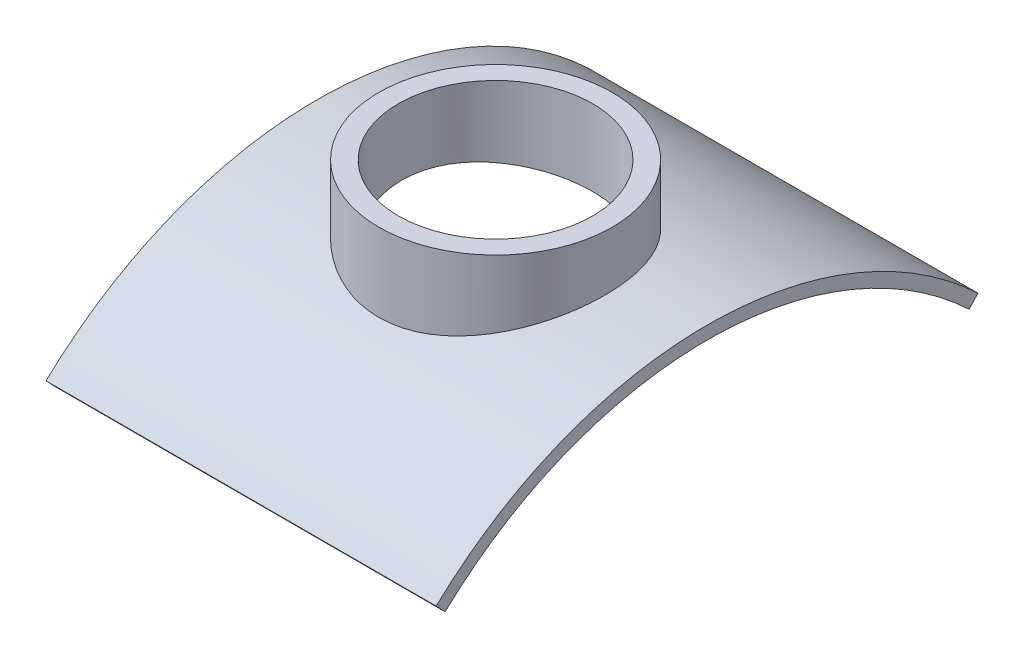
SolidWorks part; units mm, degrees
ref_plane "Front Plane" through (0, 0, 0) normal (0, 0, 1) x (1, 0, 0)
ref_plane "Top Plane" through (0, 0, 0) normal (0, 1, 0) x (1, 0, 0)
ref_plane "Right Plane" through (0, 0, 0) normal (1, 0, 0) x (0, 0, -1)
sketch "Sketch1" plane through (0, 0, 0) normal (1, 0, 0) x (0, 0, -1)
  arc A0 (-40.3747, 0) -> (65.4482, 0) centre (12.5367, -55.8968) cw
extrude "Extrude-Thin1" add sketch "Sketch1" against normal blind 76.2 thin
ref_plane "Plane1" through (0, 31.75, 0) normal (0, 1, 0) x (-1, 0, 0)
sketch "Sketch2" plane through (0, 31.75, 0) normal (0, 1, 0) x (-1, 0, 0)
  circle A0 centre (37.9311, -9.1593) radius 22.7978
extrude "Extrude1" add sketch "Sketch2" against normal up to body
sketch "Sketch3" plane through (0, 31.75, 0) normal (0, 1, 0) x (-1, 0, 0)
  circle A0 centre (37.9311, -9.1593) radius 18.9847
extrude "Extrude2" cut sketch "Sketch3" against normal blind 76.2
